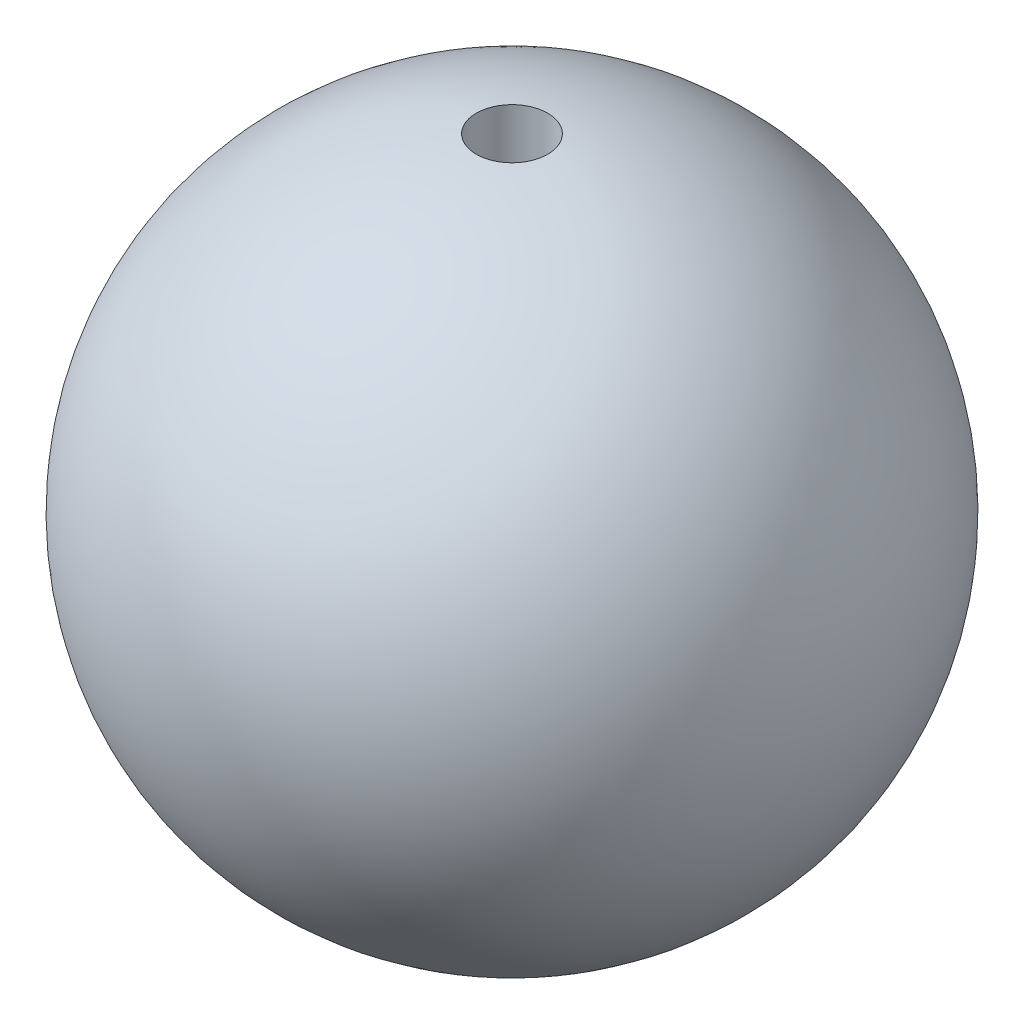
SolidWorks part; units mm, degrees
ref_plane "前视基准面" through (0, 0, 0) normal (0, 0, 1) x (1, 0, 0)
ref_plane "上视基准面" through (0, 0, 0) normal (0, 1, 0) x (1, 0, 0)
ref_plane "右视基准面" through (0, 0, 0) normal (1, 0, 0) x (0, 0, -1)
sketch "草图1" plane through (0, 0, 0) normal (0, 0, 1) x (1, 0, 0)
  line L0 (0, 0) -> (0, 242193.4874) construction
  line L1 (-100, 918.5728) -> (-100, 149.6663)
  line L2 (-100, -340.7051) -> (-100, -918.5728)
  arc A0 (-100, 149.6663) -> (-169.3259, -61.0634) centre (0, 0) ccw
  arc A1 (-169.3259, -61.0634) -> (-100, -340.7051) centre (0, -167.5) ccw
  arc A2 (-100, 918.5728) -> (-100, -918.5728) centre (0, 0) ccw
  point P12 (0, 0)
  point P13 (0, 0)
  dimension "D1" = 180
  dimension "D2" = 200
  dimension "D5" = 924
  dimension "D3" = 200
  dimension "D4" = 167.5
revolve "旋转1" add sketch "草图1" angle 360 about L0
